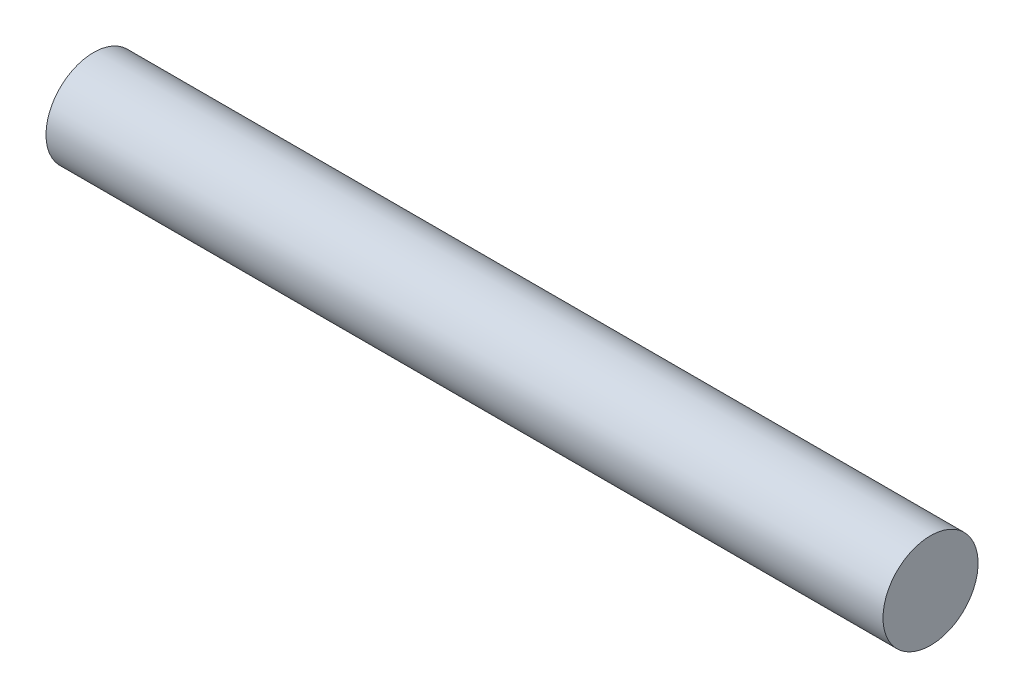
SolidWorks part; units mm, degrees
ref_plane "Front Plane" through (0, 0, 0) normal (0, 0, 1) x (1, 0, 0)
ref_plane "Top Plane" through (0, 0, 0) normal (0, 1, 0) x (1, 0, 0)
ref_plane "Right Plane" through (0, 0, 0) normal (1, 0, 0) x (0, 0, -1)
sketch "Sketch1" plane through (0, 0, 0) normal (1, 0, 0) x (0, 0, -1)
  circle A0 centre (0, 0) radius 2.5
  dimension "D1" = 5
extrude "Boss-Extrude1" add sketch "Sketch1" along normal blind 44
